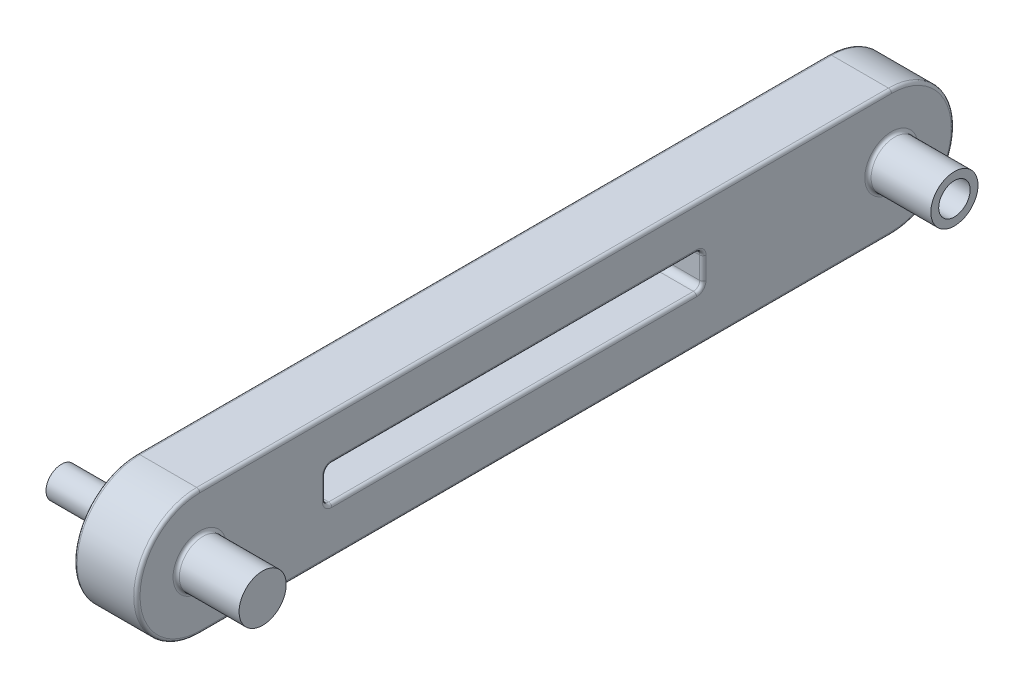
SolidWorks part; units mm, degrees
ref_plane "前视基准面" through (0, 0, 0) normal (0, 0, 1) x (1, 0, 0)
ref_plane "上视基准面" through (0, 0, 0) normal (0, 1, 0) x (1, 0, 0)
ref_plane "右视基准面" through (0, 0, 0) normal (1, 0, 0) x (0, 0, -1)
other "Configuration Table"
sketch "草图1" plane through (0, 0, 0) normal (1, 0, 0) x (0, 0, -1)
  line L0 (0, 0) -> (110, 0) construction
  line L1 (0, 10) -> (110, 10)
  line L2 (0, -10) -> (110, -10)
  arc A0 (0, 10) -> (0, -10) centre (0, 0) ccw
  arc A1 (110, -10) -> (110, 10) centre (110, 0) ccw
  circle A2 centre (0, 0) radius 3.75
  circle A3 centre (110, 0) radius 3.75
  point P3 (55, 0)
  dimension "D2" = 10
  dimension "D3" = 7.5
  dimension "D4" = 7.5
  dimension "D1" = 110
extrude "凸台-拉伸1" add sketch "草图1" along normal blind 10
sketch "草图2" plane through (10, 0, 0) normal (1, 0, 0) x (0, 0, -1)
  circle A0 centre (110, 0) radius 3.75 construction
  circle A1 centre (0, 0) radius 3.75 construction
  circle A2 centre (110, 0) radius 3.75
  circle A3 centre (0, 0) radius 3.75
extrude "凸台-拉伸2" add sketch "草图2" along normal mid plane 20
sketch "草图3" plane through (0, 0, 0) normal (-1, 0, 0) x (0, 0, 1)
  circle A0 centre (-110, 0) radius 2.5 construction
  circle A1 centre (-110, 0) radius 2.5
extrude "切除-拉伸1" cut sketch "草图3" against normal through all
sketch "草图4" plane through (0, 0, 0) normal (-1, 0, 0) x (0, 0, 1)
  line L0 (-80, 3) -> (-20, 3)
  line L1 (-20, 3) -> (-20, -2.5)
  line L2 (-20, -2.5) -> (-80, -2.5)
  line L3 (-80, -2.5) -> (-80, 3)
  line L4 (0, 10) -> (0, -10)
  line L5 (-110, 10) -> (0, 10) construction
  dimension "D1" = 20
  dimension "D2" = 7
  dimension "D3" = 5.5
  dimension "D4" = 60
extrude "切除-拉伸2" cut sketch "草图4" against normal blind 10 contours L3 L2 L1 L0
fillet "圆角1" radius 1 4 edges at (5, -2.5, -20) (5, 3, -20) (5, 3, -80) (5, -2.5, -80)
fillet "圆角2" radius 0.5 27 edges at (10, 2.7071, -20.2929) (10, 0.25, -20) (10, -2.2071, -20.2929) (10, -2.5, -50) (10, -2.2071, -79.7071) (10, 0.25, -80) (10, 2.7071, -79.7071) (10, 3, -50) (10, 0, -113.75) (10, 10, -55) (10, 0, -120) (10, -10, -55) (10, 0, 10) (10, 0, -3.75) (0, -2.2071, -20.2929) (0, 0.25, -20) (0, 2.7071, -20.2929) (0, 3, -50) (0, 2.7071, -79.7071) (0, 0.25, -80) (0, -2.2071, -79.7071) (0, -2.5, -50) (0, 0, -107.5) (0, -10, -55) (0, 0, -120) (0, 10, -55) (0, 0, 10)
sketch "草图5" plane through (0, 0, 0) normal (-1, 0, 0) x (0, 0, 1)
  circle A0 centre (0, 0) radius 2.45
  dimension "D1" = 4.9
extrude "凸台-拉伸3" add sketch "草图5" along normal blind 12
